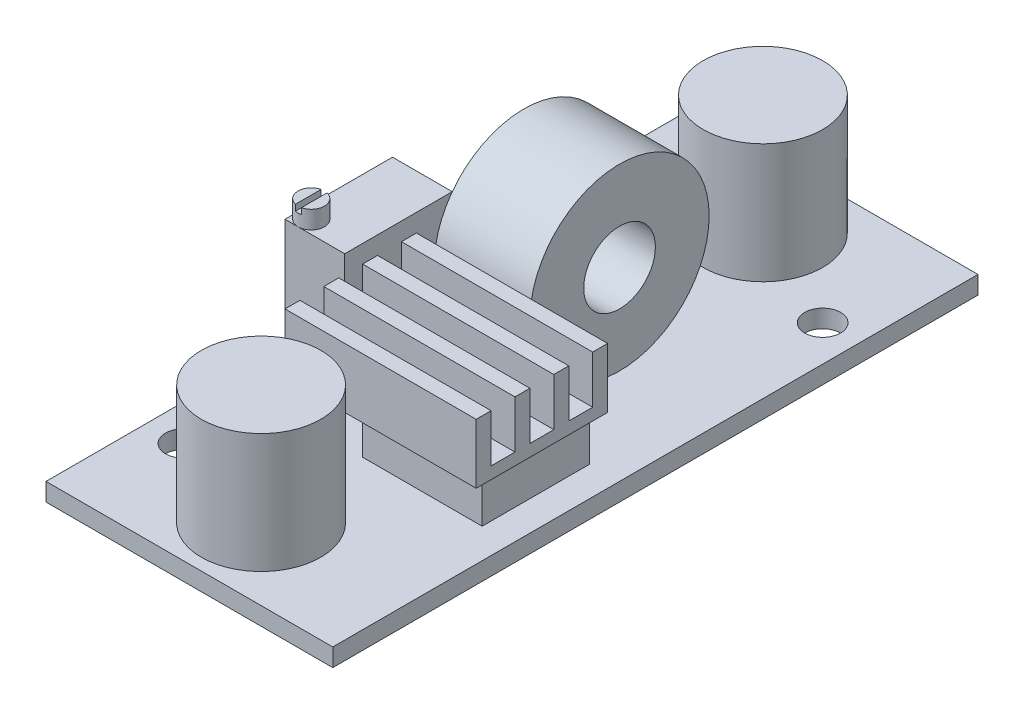
SolidWorks part; units mm, degrees
ref_plane "Front" through (0, 0, 0) normal (0, 0, 1) x (1, 0, 0)
ref_plane "Top" through (0, 0, 0) normal (0, 1, 0) x (1, 0, 0)
ref_plane "Right" through (0, 0, 0) normal (1, 0, 0) x (0, 0, -1)
sketch "Sketch1" plane through (0, 0, 0) normal (0, 1, 0) x (1, 0, 0)
  line L1 (-12, 27) -> (12, 27)
  line L2 (-12, 27) -> (-12, -27)
  line L3 (-12, -27) -> (12, -27)
  line L4 (12, 27) -> (12, -27)
  line L5 (-12, 27) -> (12, -27) construction
  line L6 (-12, -27) -> (12, 27) construction
  point P0 (0, 0)
  dimension "D1" = 54
  dimension "D2" = 24
extrude "Boss-Extrude1" add sketch "Sketch1" along normal blind 1.5
sketch "Sketch2" plane through (0, 1.5, 0) normal (0, 1, 0) x (1, 0, 0)
  line L0 (12, 27) -> (-12, 27) construction
  line L1 (-12, -27) -> (12, -27) construction
  line L2 (12, -27) -> (12, 27) construction
  line L3 (-12, 27) -> (-12, -27) construction
  circle A0 centre (9, 17) radius 1.5
  circle A1 centre (-9, -18.5) radius 1.5
  dimension "D1" = 3
  dimension "D2" = 10
  dimension "D3" = 8.5
  dimension "D4" = 3
  dimension "D5" = 3
extrude "Cut-Extrude1" cut sketch "Sketch2" against normal through all
sketch "Sketch3" plane through (0, 1.5, 0) normal (0, 1, 0) x (1, 0, 0)
  line L0 (-12, -27) -> (12, -27) construction
  line L1 (0, 0) -> (12, 0) construction
  line L2 (12, -27) -> (12, 27) construction
  circle A1 centre (0, -21) radius 5
  circle A2 centre (0, 21) radius 5
  dimension "D1" = 10
  dimension "D2" = 6
extrude "Boss-Extrude2" add sketch "Sketch3" along normal blind 10
sketch "Sketch4" plane through (0, 1.5, 0) normal (0, 1, 0) x (1, 0, 0)
  line L0 (-12, 27) -> (-12, -27) construction
  line L1 (-11, 1) -> (-6, 1)
  line L2 (-11, 1) -> (-11, -8)
  line L3 (-11, -8) -> (-6, -8)
  line L4 (-6, 1) -> (-6, -8)
  line L5 (-12, -27) -> (12, -27) construction
  dimension "D1" = 9
  dimension "D2" = 5
  dimension "D3" = 1
  dimension "D4" = 19
extrude "Boss-Extrude3" add sketch "Sketch4" along normal blind 10
sketch "Sketch5" plane through (0, 11.5, 0) normal (0, 1, 0) x (-1, 0, 0)
  line L2 (11, 8) -> (6, 8) construction
  line L3 (11, -1) -> (11, 8) construction
  circle A0 centre (9.9, 6.9) radius 1.1
  dimension "D1" = 2.2
extrude "Boss-Extrude4" add sketch "Sketch5" along normal blind 1.5 separate body
sketch "Sketch6" plane through (0, 13, 0) normal (0, 1, 0) x (-1, 0, 0)
  line L1 (9.65, 8) -> (10.15, 8)
  line L2 (9.65, 8) -> (9.65, 5.8)
  line L3 (9.65, 5.8) -> (10.15, 5.8)
  line L4 (10.15, 8) -> (10.15, 5.8)
  line L5 (9.9, 8) -> (9.9, 6.9) construction
  circle A1 centre (9.9, 6.9) radius 1.1 construction
  dimension "D1" = 0.5
extrude "Cut-Extrude2" cut sketch "Sketch6" against normal blind 0.5
sketch "Sketch7" plane through (0, 0, 0) normal (1, 0, 0) x (0, 0, -1)
  line L0 (-27, 1.5) -> (27, 1.5) construction
  line L1 (27, 1.5) -> (27, 0) construction
  circle A0 centre (5, 9) radius 7.5
  circle A1 centre (5, 9) radius 3
  dimension "D1" = 15
  dimension "D2" = 6
  dimension "D3" = 22
extrude "Boss-Extrude5" add sketch "Sketch7" along normal mid plane 8 separate body
sketch "Sketch8" plane through (0, 1.5, 0) normal (0, 1, 0) x (1, 0, 0)
  line L0 (-12, -27) -> (12, -27) construction
  line L1 (-0.5, -3) -> (9.5, -3)
  line L2 (-0.5, -3) -> (-0.5, -12)
  line L3 (-0.5, -12) -> (9.5, -12)
  line L4 (9.5, -3) -> (9.5, -12)
  line L5 (12, -27) -> (12, 27) construction
  dimension "D1" = 9
  dimension "D2" = 15
  dimension "D3" = 2.5
  dimension "D4" = 10
extrude "Boss-Extrude6" add sketch "Sketch8" along normal blind 4.5
sketch "Sketch9" plane through (0, 6, 0) normal (0, 1, 0) x (1, 0, 0)
  line L1 (-5, -3) -> (11, -3)
  line L2 (-5, -3) -> (-5, -14)
  line L3 (-5, -14) -> (11, -14)
  line L4 (11, -3) -> (11, -14)
  line L5 (12, -27) -> (12, 27) construction
  line L6 (-12, -27) -> (12, -27) construction
  dimension "D1" = 11
  dimension "D2" = 16
  dimension "D3" = 1
  dimension "D4" = 13
extrude "Boss-Extrude7" add sketch "Sketch9" along normal blind 5 separate body
sketch "Sketch10" plane through (11, 0, 0) normal (1, 0, 0) x (0, 0, -1)
  line L0 (-14, 11) -> (-3, 11) construction
  line L1 (-12.75, 11) -> (-10.75, 11)
  line L2 (-12.75, 11) -> (-12.75, 7)
  line L3 (-12.75, 7) -> (-10.75, 7)
  line L4 (-10.75, 11) -> (-10.75, 7)
  line L5 (-8.5, 7) -> (-8.5, 6) construction
  line L6 (-9.5, 11) -> (-7.5, 11)
  line L7 (-9.5, 11) -> (-9.5, 7)
  line L8 (-9.5, 7) -> (-7.5, 7)
  line L9 (-7.5, 11) -> (-7.5, 7)
  line L14 (-14, 6) -> (-3, 6) construction
  line L15 (-6.25, 11) -> (-6.25, 7)
  line L16 (-4.25, 7) -> (-6.25, 7)
  line L17 (-4.25, 11) -> (-4.25, 7)
  line L18 (-4.25, 11) -> (-6.25, 11)
  line L19 (-12.75, 7) -> (-14, 7) construction
  line L20 (-14, 11) -> (-14, 6) construction
  line L21 (-10.75, 7) -> (-9.5, 7) construction
  dimension "D1" = 2
  dimension "D2" = 1
extrude "Cut-Extrude3" cut sketch "Sketch10" against normal up to next (16 mm away)
